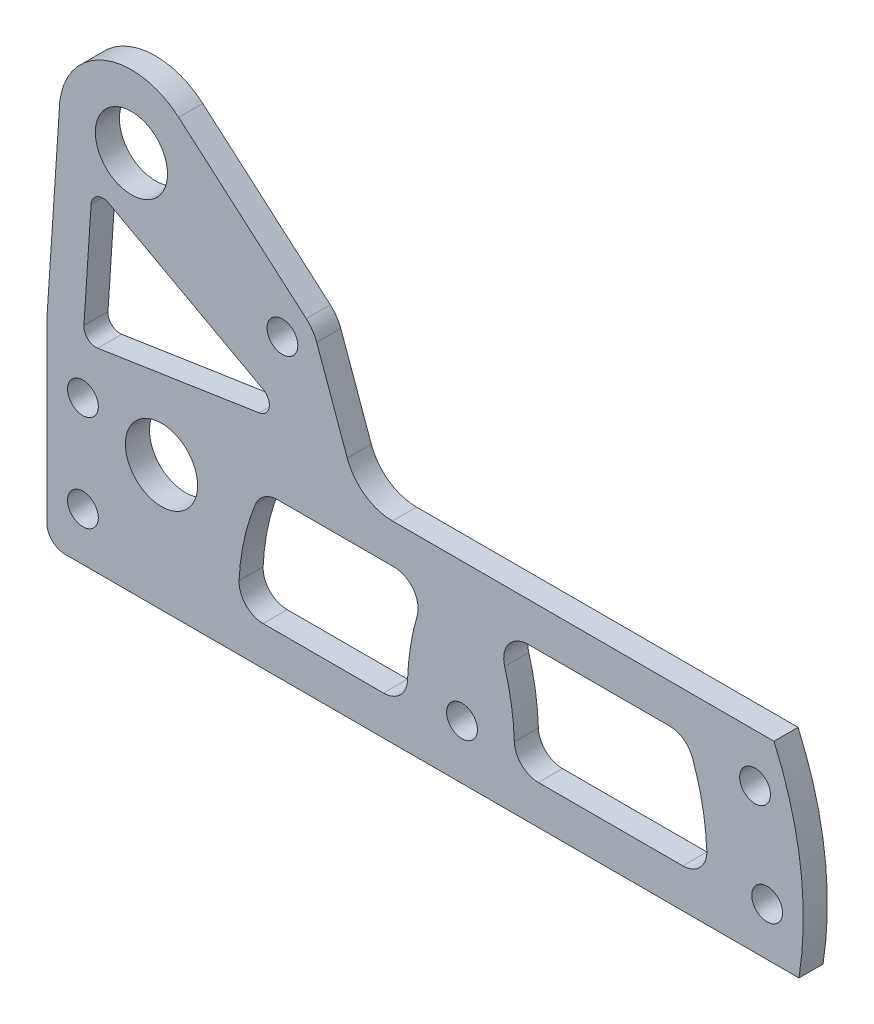
SolidWorks part; units mm, degrees
ref_plane "Front Plane" through (0, 0, 0) normal (0, 0, 1) x (1, 0, 0)
ref_plane "Top Plane" through (0, 0, 0) normal (0, 1, 0) x (1, 0, 0)
ref_plane "Right Plane" through (0, 0, 0) normal (1, 0, 0) x (0, 0, -1)
sketch "Sketch1" plane through (0, 0, 0) normal (0, 0, 1) x (1, 0, 0)
  line L0 (0, 0) -> (-99.2187, 0)
  line L1 (-99.2187, 0) -> (-99.2187, 25.4)
  line L3 (-63.6157, 40.8134) -> (-58.0846, 25.4)
  line L4 (-58.0846, 25.4) -> (-3.2973, 25.4)
  line L5 (-5.795, 19.05) -> (-1.0325, 19.05) construction
  line L6 (-4.1991, 6.35) -> (0.5634, 6.35) construction
  line L7 (-81.8207, 57.4052) -> (-64.9924, 42.8228)
  line L8 (-59.5937, 29.6052) -> (-72.1795, 64.6777) construction
  line L9 (-99.2082, 25.7183) -> (-97.5834, 50.2068)
  arc A0 (-3.2973, 25.4) -> (0, 0) centre (-44.45, 7.1437) cw
  circle A1 centre (-44.45, 7.1437) radius 2.032
  circle A2 centre (-44.45, 7.1437) radius 34.925 construction
  circle A3 centre (-44.45, 7.1437) radius 23.8125 construction
  circle A4 centre (-84.0897, 16.5735) radius 16.9333 construction
  circle A5 centre (-84.0897, 16.5735) radius 4.7625
  circle A6 centre (-88.0584, 50.2068) radius 16.9333 construction
  circle A7 centre (-88.0584, 50.2068) radius 4.7625
  circle A8 centre (-4.1991, 6.35) radius 2.032
  circle A9 centre (-5.795, 19.05) radius 2.032
  circle A10 centre (-94.4562, 6.35) radius 2.032
  circle A11 centre (-94.4562, 19.05) radius 2.032
  arc A12 (-64.9924, 42.8228) -> (-63.6157, 40.8134) centre (-68.1407, 39.1896) cw
  arc A14 (-97.5834, 50.2068) -> (-81.8207, 57.4052) centre (-88.0584, 50.2068) cw
  arc A15 (-99.2187, 25.4) -> (-99.2082, 25.7183) centre (-94.4112, 25.4) cw
  point P41 (-68.1407, 39.1896)
  dimension "D6" = 69.85
  dimension "D7" = 47.625
  dimension "D8" = 33.8667
  dimension "D19" = 4.064
  dimension "D21" = 9.525
  dimension "D9" = 9.525
  dimension "D3" = 25.4
  dimension "D4" = 7.1437
  dimension "D10" = 44.45
  dimension "D14" = 16.5735
  dimension "D16" = 12.7
  dimension "D17" = 4.7625
  dimension "D18" = 4.7625
  dimension "D5" = 3.9688
  dimension "D12" = 25.4
  dimension "D11" = 6.35
  dimension "D13" = 54.7687
extrude "Boss-Extrude1" add sketch "Sketch1" along normal blind 3.175
fillet "Fillet1" radius 6.35 1 edges at (-58.0846, 25.4, 1.5875)
sketch "Sketch2" plane through (0, 0, 3.175) normal (0, 0, 1) x (1, 0, 0)
  circle A0 centre (-68.1407, 39.1896) radius 2.032 construction
  circle A1 centre (-68.1407, 39.1896) radius 2.032
extrude "Cut-Extrude1" cut sketch "Sketch2" against normal through all
fillet "Fillet2" radius 2.3876 1 edges at (-99.2187, 0, 1.5875)
sketch "Sketch4" plane through (0, 0, 0) normal (0, 0, -1) x (-1, 0, 0)
  line L0 (99.2187, 25.4) -> (99.2187, 2.3876) construction
  line L1 (25.1465, 20.25) -> (25.1465, 25.4) construction
  line L2 (14.9062, 20.25) -> (40.3062, 20.25)
  line L3 (12.1912, 5.15) -> (37.5912, 5.15)
  line L4 (3.2973, 25.4) -> (53.6169, 25.4) construction
  line L5 (25.1465, 5.15) -> (25.1465, 0) construction
  line L6 (96.8311, 0) -> (0, 0) construction
  line L7 (71.2109, 28.9527) -> (92.5015, 25.6988)
  line L8 (73.8187, 5.15) -> (51.5937, 5.15)
  line L9 (70.8076, 20.25) -> (48.8787, 20.25)
  line L10 (94.3253, 27.3731) -> (93.3751, 41.6943)
  line L11 (91.0324, 42.9837) -> (70.692, 31.9165)
  line L12 (97.5834, 50.2068) -> (99.2082, 25.7183) construction
  arc A0 (40.3062, 20.25) -> (37.5912, 5.15) centre (69.85, 7.1437) ccw
  arc A1 (70.8076, 20.25) -> (73.8187, 5.15) centre (44.45, 7.1437) cw
  arc A2 (14.9062, 20.25) -> (12.5391, 2.0152) centre (44.45, 7.1437) ccw
  arc A3 (14.9062, 20.25) -> (12.1912, 5.15) centre (44.45, 7.1437) ccw
  arc A4 (48.8787, 20.25) -> (51.5937, 5.15) centre (19.3349, 7.1437) cw
  circle A6 centre (88.0584, 50.2068) radius 4.7625 construction
  arc A7 (93.3751, 41.6943) -> (91.0324, 42.9837) centre (91.7911, 41.5892) ccw
  arc A8 (70.692, 31.9165) -> (71.2109, 28.9527) centre (71.4507, 30.522) ccw
  arc A9 (92.5015, 25.6988) -> (94.3253, 27.3731) centre (92.7413, 27.268) ccw
  point P22 (66.5532, 29.6646)
  point P23 (93.2109, 44.169)
  point P24 (94.4562, 25.4)
  point P31 (68.1407, 39.1896)
  point P32 (94.4562, 19.05)
  point P34 (88.0584, 50.2068)
  point P46 (93.2109, 44.169)
  point P49 (66.5532, 29.6646)
  point P52 (94.4562, 25.4)
  dimension "D5" = 1.5875
  dimension "D8" = 1.5875
  dimension "D2" = 25.4
  dimension "D3" = 25.4
  dimension "D4" = 22.225
  dimension "D6" = 7.9375
  dimension "D7" = 6.35
  dimension "D9" = 9.525
  dimension "D1" = 12.7
extrude "Cut-Extrude2" cut sketch "Sketch4" against normal up to next
fillet "Fillet3" radius 3.175 8 edges at (-51.5937, 5.15, 1.5875) (-73.8187, 5.15, 1.5875) (-70.8076, 20.25, 1.5875) (-48.8787, 20.25, 1.5875) (-37.5912, 5.15, 1.5875) (-12.1912, 5.15, 1.5875) (-14.9062, 20.25, 1.5875) (-40.3062, 20.25, 1.5875)
equation "\"D7@Sketch1\"=45/24"
equation "\"D8@Sketch1\"=32/24"
